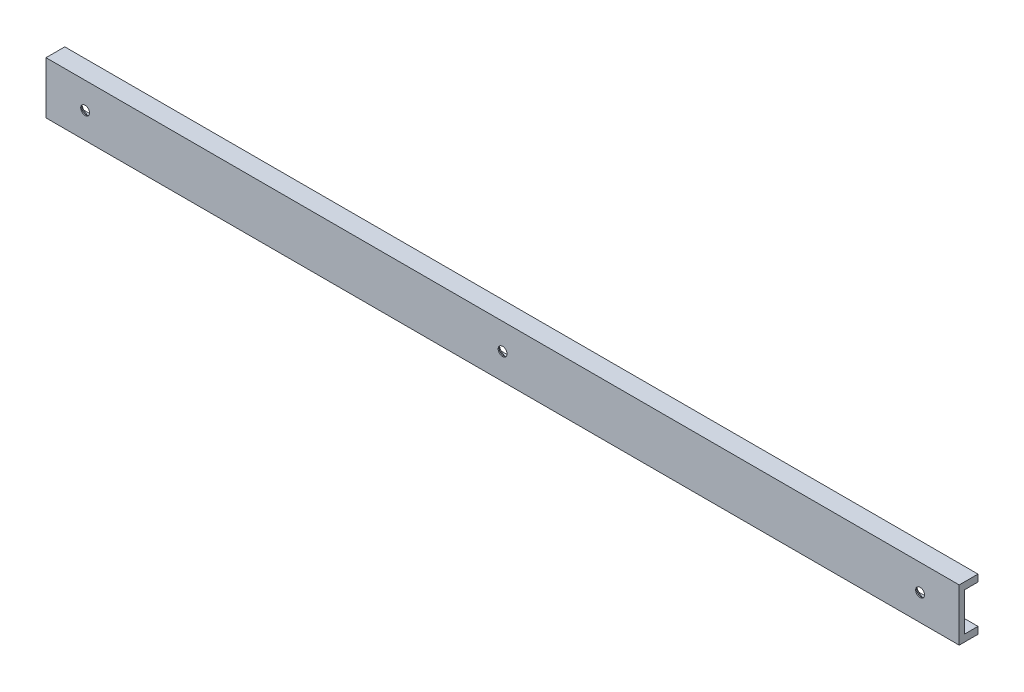
SolidWorks part; units mm, degrees
material "6061 合金"
ref_plane "前视基准面" through (0, 0, 0) normal (0, 0, 1) x (1, 0, 0)
ref_plane "上视基准面" through (0, 0, 0) normal (0, 1, 0) x (1, 0, 0)
ref_plane "右视基准面" through (0, 0, 0) normal (1, 0, 0) x (0, 0, -1)
sketch "草图1" plane through (0, 0, 0) normal (1, 0, 0) x (0, 0, -1)
  line L0 (0, -10) -> (0, 10)
  line L1 (0, 10) -> (7.2, 10)
  line L2 (7.2, 10) -> (7.2, 7.35)
  line L3 (7.2, 7.35) -> (2, 7.35)
  line L4 (2, 7.35) -> (2, -7.35)
  line L5 (2, -7.35) -> (7.2, -7.35)
  line L6 (7.2, -7.35) -> (7.2, -10)
  line L7 (7.2, -10) -> (0, -10)
  line L8 (0, 0) -> (2, 0) construction
  point P4 (0, 0)
  dimension "D1" = 7.2
  dimension "D2" = 20
  dimension "D3" = 14.7
  dimension "D4" = 2
extrude "凸台-拉伸1" add sketch "草图1" along normal mid plane 350
sketch "草图3" plane through (0, 0, -2) normal (0, 0, -1) x (-1, 0, 0)
  line L0 (-175, 0) -> (-160, 0) construction
  line L1 (-175, -7.35) -> (-175, 7.35) construction
  dimension "D1" = 15
hole_wizard "M3 开槽半沉头木螺钉的锥形沉头孔1" positions "草图4" profile "草图5" countersink size "M3" standard "GB" end condition through all
sketch "草图4" plane through (0, 0, -2) normal (0, 0, -1) x (-1, 0, 0)
  point P0 (-160, 0)
sketch "草图5" plane through (160, 0, -2) normal (1, 0, 0) x (0, 1, 0)
  line L0 (0, 0) -> (0, 2)
  line L1 (0, 2) -> (1.7, 2)
  line L2 (1.7, 2) -> (1.7, 1.6)
  line L3 (1.7, 1.6) -> (3.3, 0)
  line L5 (3.3, 0) -> (0, 0)
  line L6 (-1.7, 1.6) -> (-3.3, 0) construction
  line L11 (0, -6.35) -> (0, 107.95) construction
  dimension "通孔孔直径" = 3.4
  dimension "通孔孔深度" = 2
  dimension "近端锥形沉头孔直径" = 6.6
  dimension "近端锥形沉头孔角度" = 90
pattern_linear "阵列(线性)1" count 3 spacing 160 along (-1, 0, 0) of "M3 开槽半沉头木螺钉的锥形沉头孔1"
